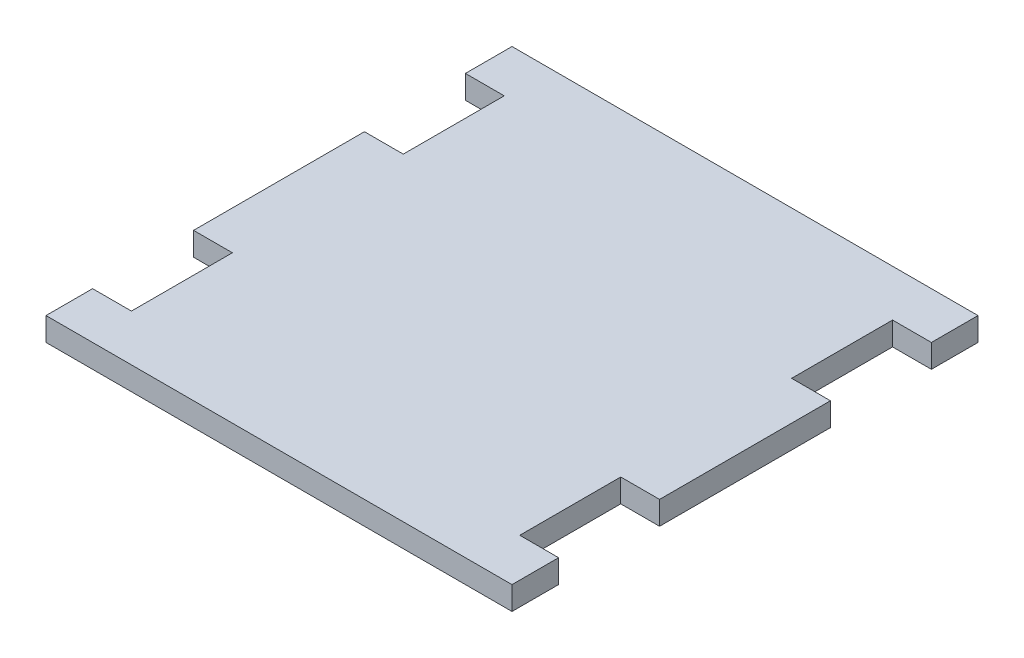
SolidWorks part; units mm, degrees
ref_plane "Front Plane" through (0, 0, 0) normal (0, 0, 1) x (1, 0, 0)
ref_plane "Top Plane" through (0, 0, 0) normal (0, 1, 0) x (1, 0, 0)
ref_plane "Right Plane" through (0, 0, 0) normal (1, 0, 0) x (0, 0, -1)
sketch "Sketch1" plane through (0, 0, 0) normal (0, 1, 0) x (1, 0, 0)
  line L5 (-150, -150) -> (150, -150)
  line L6 (-150, -150) -> (-150, 150)
  line L7 (-150, 150) -> (150, 150)
  line L8 (150, -150) -> (150, 150)
  line L9 (-150, -150) -> (150, 150) construction
  line L10 (-150, 150) -> (150, -150) construction
  point P0 (0, 0)
  dimension "D1" = 300
  dimension "D2" = 300
extrude "Boss-Extrude1" add sketch "Sketch1" along normal blind 15
sketch "Sketch2" plane through (0, 15, 0) normal (0, 1, 0) x (1, 0, 0)
  line L0 (-150, 150) -> (-150, -150) construction
  line L1 (-150, 120) -> (-125, 120)
  line L2 (-150, 120) -> (-150, 55)
  line L3 (-150, 55) -> (-125, 55)
  line L4 (-125, 120) -> (-125, 55)
  line L5 (150, -150) -> (150, 150) construction
  line L6 (150, 120) -> (125, 120)
  line L7 (150, 120) -> (150, 55)
  line L8 (150, 55) -> (125, 55)
  line L9 (125, 120) -> (125, 55)
  line L10 (-150, -150) -> (150, -150) construction
  line L11 (-150, -55) -> (-125, -55)
  line L12 (-150, -55) -> (-150, -120)
  line L13 (-150, -120) -> (-125, -120)
  line L14 (-125, -55) -> (-125, -120)
  line L15 (150, -55) -> (125, -55)
  line L16 (150, -55) -> (150, -120)
  line L17 (150, -120) -> (125, -120)
  line L18 (125, -55) -> (125, -120)
  line L19 (150, 150) -> (-150, 150) construction
  dimension "D1" = 65
  dimension "D2" = 25
  dimension "D3" = 25
  dimension "D4" = 65
  dimension "D5" = 25
  dimension "D6" = 65
  dimension "D7" = 65
  dimension "D8" = 25
  dimension "D9" = 30
  dimension "D10" = 30
  dimension "D11" = 30
  dimension "D12" = 30
extrude "Cut-Extrude1" cut sketch "Sketch2" against normal blind 125
